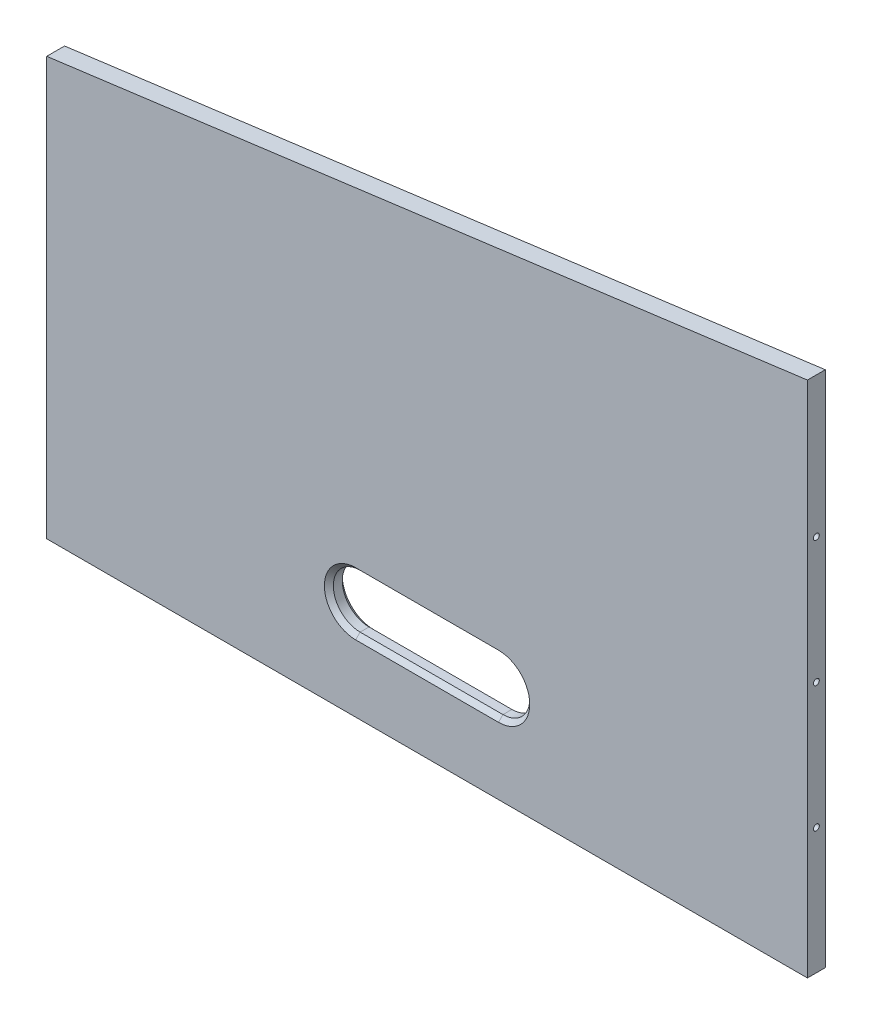
SolidWorks part; units mm, degrees
material "Bakelite Black"
ref_plane "Front" through (0, 0, 0) normal (0, 0, 1) x (1, 0, 0)
ref_plane "Top" through (0, 0, 0) normal (0, 1, 0) x (1, 0, 0)
ref_plane "Right" through (0, 0, 0) normal (1, 0, 0) x (0, 0, -1)
sketch "Sketch1" plane through (0, 0, 0) normal (0, 0, 1) x (1, 0, 0)
  line L0 (0, 234) -> (0, 290)
  line L1 (0, 0) -> (-426, 0)
  line L2 (0, 0) -> (0, 234)
  line L4 (-426, 0) -> (-426, 234)
  line L5 (0, 290) -> (-426, 234)
  dimension "D1" = 426
  dimension "D2" = 234
  dimension "D3" = 56
extrude "Boss-Extrude1" add sketch "Sketch1" along normal blind 10
ref_plane "Plane1" through (-213, 0, 0) normal (1, 0, 0) x (0, 0, -1)
sketch "Sketch2" plane through (0, 0, 0) normal (0, 0, -1) x (-1, 0, 0)
  line L0 (426, 0) -> (0, 0) construction
  line L1 (173, 70) -> (253, 70)
  line L3 (173, 40) -> (253, 40)
  line L5 (173, 70) -> (253, 40) construction
  line L6 (173, 40) -> (253, 70) construction
  arc A0 (173, 70) -> (173, 40) centre (173, 55) ccw
  arc A1 (253, 40) -> (253, 70) centre (253, 55) ccw
  point P0 (213, 55)
  point P8 (213, 0)
  dimension "D1" = 80
  dimension "D2" = 30
  dimension "D3" = 40
extrude "Cut-Extrude1" cut sketch "Sketch2" against normal through all
chamfer "Chamfer1" distance 2.5 angle 45 8 edges at (-268, 55, 0) (-213, 40, 0) (-158, 55, 0) (-213, 70, 0) (-268, 55, 10) (-213, 40, 10) (-158, 55, 10) (-213, 70, 10)
hole_wizard "M4x0.7 Tapped Hole1" positions "Sketch3" profile "Sketch4" tap size "M4x0.7" standard "ANSI Metric"
sketch "Sketch3" plane through (0, 0, 0) normal (0, -1, 0) x (-1, 0, 0)
  line L0 (213, 5.5) -> (213, -5.5) construction
  line L1 (426, 0) -> (0, 0) construction
  point P0 (63, -5)
  point P2 (213, -5)
  point P4 (363, -5)
  dimension "D1" = 150
  dimension "D2" = 150
  dimension "D3" = 5
sketch "Sketch4" plane through (-63, 0, 5) normal (1, 0, 0) x (0, 0, -1)
  line L0 (0, 0) -> (0, 12.9914)
  line L1 (0, 12.9914) -> (1.65, 12)
  line L2 (1.65, 12) -> (1.65, 0)
  line L5 (1.65, 0) -> (0, 0)
  line L10 (0, 12.9914) -> (-1.65, 12) construction
  line L11 (0, -6.35) -> (0, 107.95) construction
  dimension "Tap Drill Dia." = 3.3
  dimension "Tap Drill Depth" = 12
  dimension "Drill Angle" = 118
cosmetic thread "Hole Thread1" parameters "D1"=8, "D2"=4
cosmetic thread "Hole Thread2" parameters "D1"=8, "D2"=4
cosmetic thread "Hole Thread3" parameters "D1"=8, "D2"=4
hole_wizard "M4x0.7 Tapped Hole2" positions "Sketch5" profile "Sketch6" tap size "M4x0.7" standard "ANSI Metric"
sketch "Sketch5" plane through (-426, 0, 0) normal (-1, 0, 0) x (0, 0, 1)
  line L0 (0, 234) -> (0, 0) construction
  line L1 (10, 0) -> (0, 0) construction
  point P0 (5, 70.5)
  point P2 (5, 141)
  point P4 (5, 211.5)
  point P6 (0, 0)
  dimension "D1" = 5
  dimension "D2" = 70.5
  dimension "D3" = 70.5
  dimension "D4" = 70.5
sketch "Sketch6" plane through (-426, 70.5, 5) normal (0, 1, 0) x (0, 0, 1)
  line L0 (0, 0) -> (0, 12.9914)
  line L1 (0, 12.9914) -> (1.65, 12)
  line L2 (1.65, 12) -> (1.65, 0)
  line L5 (1.65, 0) -> (0, 0)
  line L10 (0, 12.9914) -> (-1.65, 12) construction
  line L11 (0, -6.35) -> (0, 107.95) construction
  dimension "Tap Drill Dia." = 3.3
  dimension "Tap Drill Depth" = 12
  dimension "Drill Angle" = 118
cosmetic thread "Hole Thread4" parameters "D1"=8, "D2"=4
cosmetic thread "Hole Thread5" parameters "D1"=8, "D2"=4
cosmetic thread "Hole Thread6" parameters "D1"=8, "D2"=4
hole_wizard "M4x0.7 Tapped Hole3" positions "Sketch7" profile "Sketch8" tap size "M4x0.7" standard "ANSI Metric"
sketch "Sketch7" plane through (0, 0, 0) normal (1, 0, 0) x (0, 0, -1)
  line L0 (0, 0) -> (0, 290) construction
  line L1 (-10, 0) -> (0, 0) construction
  point P0 (-5, 70.5)
  point P2 (-5, 141)
  point P4 (-5, 211.5)
  point P7 (0, 0)
  dimension "D1" = 5
  dimension "D2" = 70.5
  dimension "D3" = 70.5
  dimension "D4" = 70.5
sketch "Sketch8" plane through (0, 70.5, 5) normal (0, 1, 0) x (0, 0, -1)
  line L0 (0, 0) -> (0, 12.9914)
  line L1 (0, 12.9914) -> (1.65, 12)
  line L2 (1.65, 12) -> (1.65, 0)
  line L5 (1.65, 0) -> (0, 0)
  line L10 (0, 12.9914) -> (-1.65, 12) construction
  line L11 (0, -6.35) -> (0, 107.95) construction
  dimension "Tap Drill Dia." = 3.3
  dimension "Tap Drill Depth" = 12
  dimension "Drill Angle" = 118
cosmetic thread "Hole Thread7" parameters "D1"=8, "D2"=4
cosmetic thread "Hole Thread8" parameters "D1"=8, "D2"=4
cosmetic thread "Hole Thread9" parameters "D1"=8, "D2"=4
